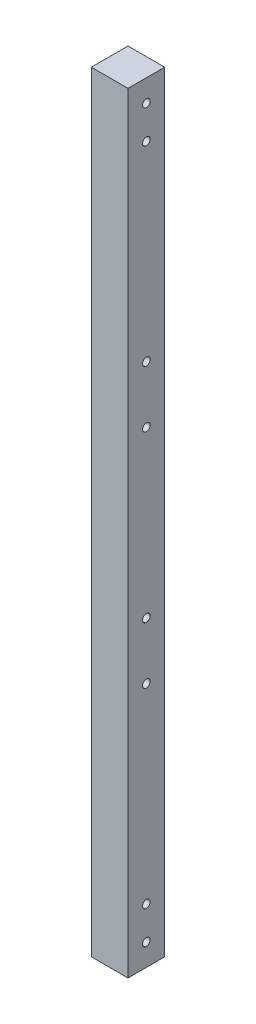
SolidWorks part; units mm, degrees
ref_plane "前视基准面" through (0, 0, 0) normal (0, 0, 1) x (1, 0, 0)
ref_plane "上视基准面" through (0, 0, 0) normal (0, 1, 0) x (1, 0, 0)
ref_plane "右视基准面" through (0, 0, 0) normal (1, 0, 0) x (0, 0, -1)
sketch "草图1" plane through (0, 0, 0) normal (0, 1, 0) x (1, 0, 0)
  line L1 (-14.8984, 2.4187) -> (5.1016, 2.4187)
  line L2 (-14.8984, 2.4187) -> (-14.8984, -17.5813)
  line L3 (-14.8984, -17.5813) -> (5.1016, -17.5813)
  line L4 (5.1016, 2.4187) -> (5.1016, -17.5813)
  dimension "D1" = 20
  dimension "D2" = 20
extrude "凸台-拉伸1" add sketch "草图1" along normal blind 420
sketch "草图3" plane through (5.1016, 0, 0) normal (1, 0, 0) x (0, 0, -1)
  line L0 (-7.5813, 420) -> (-7.5813, 408) construction
  line L1 (-17.5813, 420) -> (2.4187, 420) construction
  line L2 (-7.5813, 420) -> (-7.5813, 390) construction
  line L3 (2.4187, 210) -> (102.4704, 210) construction
  line L4 (2.4187, 420) -> (2.4187, 0) construction
  circle A0 centre (-7.5813, 390) radius 2.1
  circle A1 centre (-7.5813, 408) radius 2.1
  circle A2 centre (-7.5813, 30) radius 2.1
  circle A3 centre (-7.5813, 12) radius 2.1
  dimension "D3" = 4.2
  dimension "D4" = 4.2
  dimension "D1" = 12
  dimension "D2" = 30
extrude "切除-拉伸2" cut sketch "草图3" against normal through all
sketch "草图4" plane through (5.1016, 0, 0) normal (1, 0, 0) x (0, 0, -1)
  line L0 (-7.5813, 420) -> (-7.5813, 255) construction
  line L1 (-17.5813, 420) -> (2.4187, 420) construction
  line L3 (-7.5813, 255) -> (-7.5813, 286) construction
  line L4 (2.4187, 210) -> (-91.3179, 210) construction
  line L5 (2.4187, 420) -> (2.4187, 0) construction
  line L6 (-7.5813, 165) -> (-7.5813, 134) construction
  circle A0 centre (-7.5813, 255) radius 2.1
  circle A1 centre (-7.5813, 286) radius 2.1
  circle A2 centre (-7.5813, 134) radius 2.1
  circle A3 centre (-7.5813, 165) radius 2.1
  dimension "D2" = 4.2
  dimension "D4" = 4.2
  dimension "D1" = 165
  dimension "D3" = 31
extrude "切除-拉伸3" cut sketch "草图4" against normal through all
equation "\"4。2\"=6.35655"
